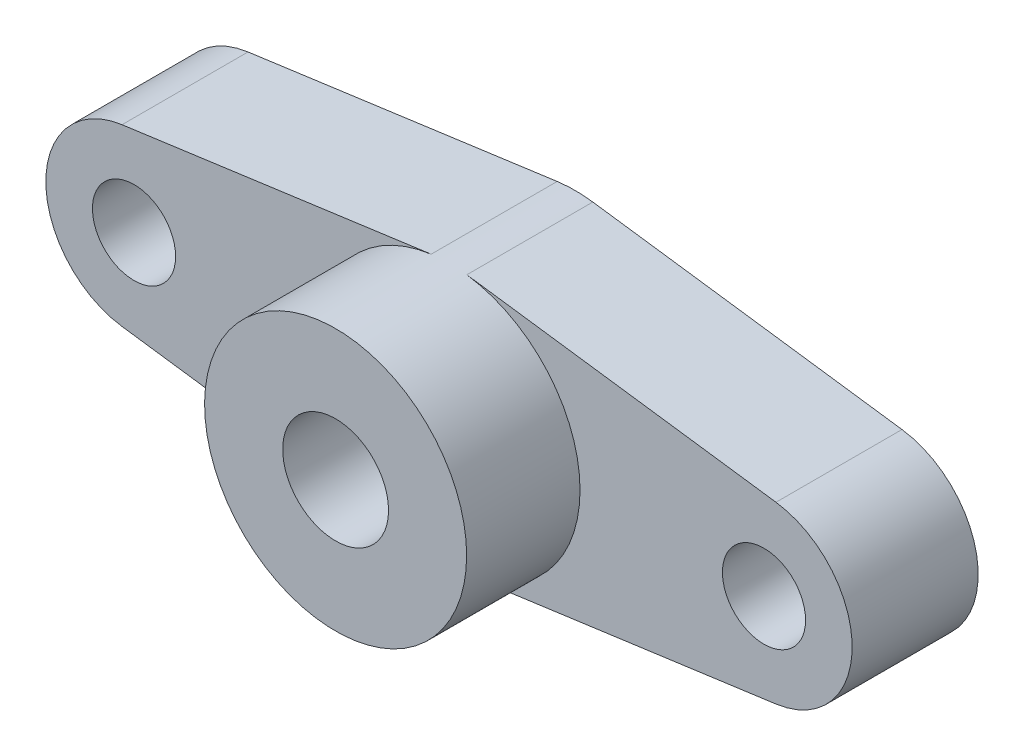
SolidWorks part; units mm, degrees
material "1060 合金"
ref_plane "前视基准面" through (0, 0, 0) normal (0, 0, 1) x (1, 0, 0)
ref_plane "上视基准面" through (0, 0, 0) normal (0, 1, 0) x (1, 0, 0)
ref_plane "右视基准面" through (0, 0, 0) normal (1, 0, 0) x (0, 0, -1)
other "Configuration Table"
sketch "草图1" plane through (0, 0, 0) normal (0, 0, 1) x (1, 0, 0)
  line L0 (-12.5, 0) -> (12.5, 0) construction
  line L2 (-16, -5.2) -> (16, -5.2)
  line L3 (-16, -5.2) -> (-16, 5.2)
  line L4 (-16, 5.2) -> (16, 5.2)
  line L5 (16, -5.2) -> (16, 5.2)
  line L6 (-16, -5.2) -> (16, 5.2) construction
  line L7 (-16, 5.2) -> (16, -5.2) construction
  circle A0 centre (-12.5, 0) radius 0.5
  circle A1 centre (12.5, 0) radius 0.5
  circle A2 centre (0, 0) radius 0.5
  circle A3 centre (-12.5, 0) radius 3.5 construction
  point P4 (0, 0)
  dimension "D1" = 1
  dimension "D2" = 1
  dimension "D4" = 5.2
  dimension "D5" = 7
  dimension "D3" = 25
extrude "凸台-拉伸1" add sketch "草图1" along normal blind 5
sketch "草图2" plane through (0, 0, 5) normal (0, 0, 1) x (1, 0, 0)
  line L0 (16, 5.2) -> (-16, 5.2) construction
  circle A0 centre (0, 0) radius 0.5
  circle A1 centre (0, 0) radius 5.2
  circle A2 centre (0, 0) radius 2.5 construction
  dimension "D1" = 1
  dimension "D3" = 5
extrude "凸台-拉伸2" add sketch "草图2" along normal blind 4.5 contours A1 A2
sketch "草图3" plane through (0, 0, 5) normal (0, 0, 1) x (1, 0, 0)
  line L0 (-16, 5.2) -> (-16, -5.2) construction
  line L1 (-0.7072, 5.1517) -> (-12.976, 3.4675)
  line L2 (-12.976, -3.4675) -> (-0.7072, -5.1517)
  line L3 (0.7072, 5.1517) -> (12.976, 3.4675)
  line L4 (0.7072, -5.1517) -> (12.976, -3.4675)
  line L6 (-16, 5.2) -> (16, 5.2)
  line L7 (-16, 5.2) -> (-16, -5.2)
  line L8 (-16, -5.2) -> (16, -5.2)
  line L9 (16, 5.2) -> (16, -5.2)
  circle A0 centre (0, 0) radius 5.2
  circle A2 centre (12.5, 0) radius 3.5
  circle A3 centre (-12.5, 0) radius 3.5
  circle A4 centre (0, 0) radius 5.2 construction
  arc M3 (0, -5.2) -> (0, 5.2) centre (0, 0) cw
  line M4 (0, 5.2) -> (-16, 5.2)
  line M5 (-16, 5.2) -> (-16, -5.2)
  line M6 (-16, -5.2) -> (0, -5.2)
extrude "切除-拉伸1" cut sketch "草图3" against normal blind 5.3 contours A3 L1 M3 M4 M5 | A3 L7 L2 M6 M3 | A2 L4 A0 L8 L9 | A2 L9 L6 A0 L3
hole_wizard "M4 螺纹孔1" positions "草图4" profile "草图5" tap size "M4" standard "GB"
sketch "草图4" plane through (0, 0, 5) normal (0, 0, 1) x (1, 0, 0)
  point P0 (-12.5, 0)
  point P3 (12.5, 0)
sketch "草图5" plane through (-12.5, 0, 5) normal (1, 0, 0) x (0, -1, 0)
  line L0 (0, 0) -> (0, 11.0914)
  line L1 (0, 11.0914) -> (1.65, 10.1)
  line L2 (1.65, 10.1) -> (1.65, 0)
  line L5 (1.65, 0) -> (0, 0)
  line L10 (0, 11.0914) -> (-1.65, 10.1) construction
  line L11 (0, -6.35) -> (0, 107.95) construction
  dimension "螺纹孔钻头直径" = 3.3
  dimension "螺纹孔钻头深度" = 10.1
  dimension "导头角度" = 118
cosmetic thread "孔螺蚊线1" parameters "D1"=8, "D2"=4
cosmetic thread "孔螺蚊线2" parameters "D1"=8, "D2"=4
hole_wizard "M5 螺纹孔1" positions "草图6" profile "草图7" tap size "M5" standard "GB"
sketch "草图6" plane through (0, 0, 9.5) normal (0, 0, 1) x (1, 0, 0)
  point P0 (0, 0)
sketch "草图7" plane through (0, 0, 9.5) normal (1, 0, 0) x (0, -1, 0)
  line L0 (0, 0) -> (0, 23.6618)
  line L1 (0, 23.6618) -> (2.1, 22.4)
  line L2 (2.1, 22.4) -> (2.1, 0)
  line L5 (2.1, 0) -> (0, 0)
  line L10 (0, 23.6618) -> (-2.1, 22.4) construction
  line L11 (0, -6.35) -> (0, 107.95) construction
  dimension "螺纹孔钻头直径" = 4.2
  dimension "螺纹孔钻头深度" = 22.4
  dimension "导头角度" = 118
cosmetic thread "孔螺蚊线3" parameters "D1"=20, "D2"=5
